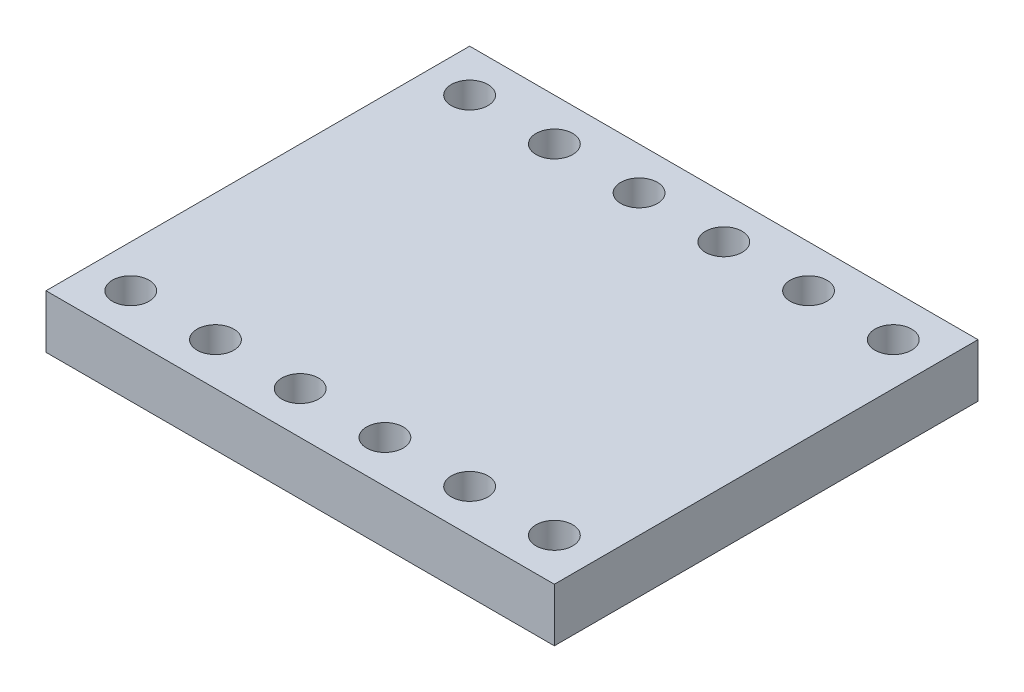
SolidWorks part; units mm, degrees
ref_plane "Front" through (0, 0, 0) normal (0, 0, 1) x (1, 0, 0)
ref_plane "Top" through (0, 0, 0) normal (0, 1, 0) x (1, 0, 0)
ref_plane "Right" through (0, 0, 0) normal (1, 0, 0) x (0, 0, -1)
sketch "Sketch1" plane through (0, 0, 0) normal (0, 1, 0) x (1, 0, 0)
  line L1 (7.62, -6.35) -> (-7.62, -6.35)
  line L2 (7.62, -6.35) -> (7.62, 6.35)
  line L3 (7.62, 6.35) -> (-7.62, 6.35)
  line L4 (-7.62, -6.35) -> (-7.62, 6.35)
  line L5 (7.62, -6.35) -> (-7.62, 6.35) construction
  line L6 (7.62, 6.35) -> (-7.62, -6.35) construction
  point P0 (0, 0)
  dimension "D1" = 15.24
  dimension "D2" = 12.7
extrude "Boss-Extrude1" add sketch "Sketch1" along normal mid plane 1.6
sketch "Sketch2" plane through (0, 0.8, 0) normal (0, 1, 0) x (1, 0, 0)
  line L0 (-7.62, 6.35) -> (-7.62, -6.35) construction
  line L1 (-7.62, -6.35) -> (7.62, -6.35) construction
  circle A0 centre (-6.35, -5.08) radius 0.55
  dimension "D1" = 1.1
  dimension "D2" = 1.27
  dimension "D3" = 1.27
extrude "Cut-Extrude1" cut sketch "Sketch2" against normal through all
pattern_linear "LPattern1" count 6 spacing 2.54 along (1, 0, 0) count 2 spacing 10.16 along (0, 0, -1) of "Cut-Extrude1"
